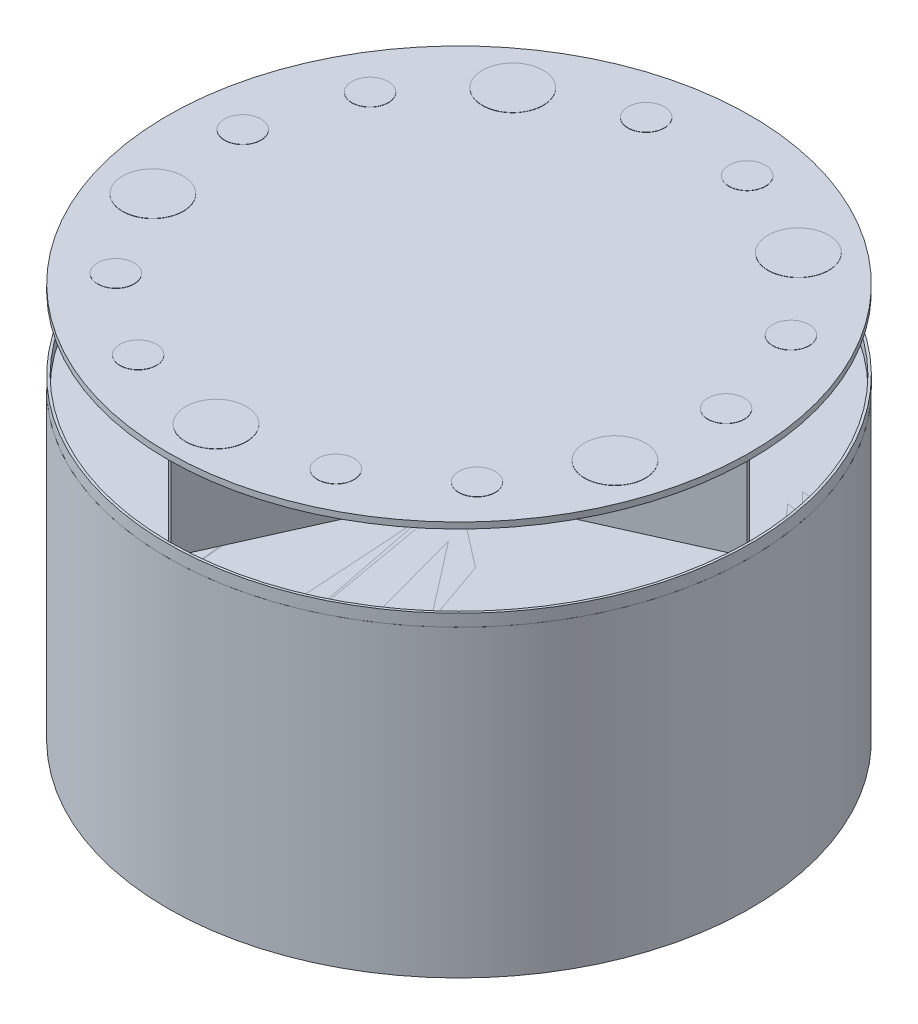
SolidWorks part; units mm, degrees
ref_plane "Front Plane" through (0, 0, 0) normal (0, 0, 1) x (1, 0, 0)
ref_plane "Top Plane" through (0, 0, 0) normal (0, 1, 0) x (1, 0, 0)
ref_plane "Right Plane" through (0, 0, 0) normal (1, 0, 0) x (0, 0, -1)
sketch "Sketch1" plane through (0, 0, 0) normal (0, 1, 0) x (1, 0, 0)
  circle A0 centre (0, 0) radius 304.8
  dimension "D1" = 609.6
extrude "Boss-Extrude1" add sketch "Sketch1" along normal blind 28.575
sketch "Sketch2" plane through (0, 28.575, 0) normal (0, 1, 0) x (1, 0, 0)
  line L0 (245.7653, 171.222) -> (201.7712, 145.822)
  line L1 (-25.4, 298.45) -> (25.4, 298.45)
  line L2 (-25.4, 298.45) -> (-25.4, 247.65)
  line L3 (-25.4, 247.65) -> (25.4, 247.65)
  line L4 (25.4, 298.45) -> (25.4, 247.65)
  line L5 (245.7653, 171.222) -> (271.1653, 127.228)
  line L6 (271.1653, 127.228) -> (227.1712, 101.828)
  line L7 (201.7712, 145.822) -> (227.1712, 101.828)
  line L8 (271.1653, -127.228) -> (227.1712, -101.828)
  line L9 (271.1653, -127.228) -> (245.7653, -171.222)
  line L10 (245.7653, -171.222) -> (201.7712, -145.822)
  line L11 (227.1712, -101.828) -> (201.7712, -145.822)
  line L12 (25.4, -298.45) -> (25.4, -247.65)
  line L13 (25.4, -298.45) -> (-25.4, -298.45)
  line L14 (-25.4, -298.45) -> (-25.4, -247.65)
  line L15 (25.4, -247.65) -> (-25.4, -247.65)
  line L16 (-245.7653, -171.222) -> (-201.7712, -145.822)
  line L17 (-245.7653, -171.222) -> (-271.1653, -127.228)
  line L18 (-271.1653, -127.228) -> (-227.1712, -101.828)
  line L19 (-201.7712, -145.822) -> (-227.1712, -101.828)
  line L20 (-271.1653, 127.228) -> (-227.1712, 101.828)
  line L21 (-271.1653, 127.228) -> (-245.7653, 171.222)
  line L22 (-245.7653, 171.222) -> (-201.7712, 145.822)
  line L23 (-227.1712, 101.828) -> (-201.7712, 145.822)
  point P4 (0, 247.65)
  point P28 (0, 0)
  dimension "D1" = 50.8
  dimension "D2" = 50.8
  dimension "D3" = 0
  dimension "D4" = 247.65
  dimension "D5" = 6
extrude "Boss-Extrude2" add sketch "Sketch2" along normal blind 63.5
sketch "Sketch3" plane through (0, 92.075, 0) normal (0, 1, 0) x (1, 0, 0)
  circle A0 centre (0, 0) radius 304.8
extrude "Boss-Extrude3" add sketch "Sketch3" along normal blind 225.425
sketch "Sketch4" plane through (0, 317.5, 0) normal (0, 1, 0) x (1, 0, 0)
  circle A0 centre (0, 0) radius 88.9
  dimension "D1" = 177.8
sketch "Sketch6" plane through (0, 317.5, 0) normal (0, 1, 0) x (1, 0, 0)
  line L1 (94.2927, 94.2927) -> (302.26, 1.27)
  line L3 (94.2927, -94.2927) -> (302.26, -1.27)
  line L4 (302.26, 1.27) -> (302.26, -1.27)
  line L16 (0, 0) -> (94.2927, -94.2927) construction
  line L17 (0, 0) -> (133.35, 0) construction
  line L19 (94.2927, -94.2927) -> (1.27, -302.26)
  line L20 (1.27, -302.26) -> (-1.27, -302.26)
  line L21 (-94.2927, -94.2927) -> (-1.27, -302.26)
  line L23 (-94.2927, -94.2927) -> (-302.26, -1.27)
  line L24 (-302.26, -1.27) -> (-302.26, 1.27)
  line L25 (-94.2927, 94.2927) -> (-302.26, 1.27)
  line L27 (-94.2927, 94.2927) -> (-1.27, 302.26)
  line L28 (-1.27, 302.26) -> (1.27, 302.26)
  line L29 (94.2927, 94.2927) -> (1.27, 302.26)
  circle A3 centre (0, 0) radius 133.35 construction
  circle A4 centre (0, 0) radius 304.8 construction
  point P22 (-2.5315, 11.0004)
  point P25 (0, 0)
  point P29 (302.26, 0)
  dimension "D1" = 171.45
  dimension "D2" = 45
  dimension "D3" = 4
  dimension "D4" = 2.54
  dimension "D5" = 302.26
extrude "Boss-Extrude8" add sketch "Sketch6" along normal blind 88.9
sketch "Sketch10" plane through (0, 406.4, 0) normal (0, 1, 0) x (1, 0, 0)
  circle A0 centre (0, 0) radius 304.8
extrude "Boss-Extrude11" add sketch "Sketch10" along normal blind 6.35
sketch "Sketch11" plane through (0, 317.5, 0) normal (0, 1, 0) x (1, 0, 0)
  circle A0 centre (0, 0) radius 304.8
  circle A1 centre (0, 0) radius 302.26
  dimension "D1" = 2.54
  dimension "D2" = 609.6
extrude "Boss-Extrude12" add sketch "Sketch11" along normal blind 12.7
sketch "Sketch9" plane through (0, 317.5, 0) normal (0, 1, 0) x (1, 0, 0)
  circle A0 centre (0, 0) radius 304.8165
  circle A1 centre (0, 0) radius 298.1787
  dimension "D1" = 596.3574
extrude "Boss-Extrude10" add sketch "Sketch9" against normal up to surface (317.5 mm away) up to face at (0, 0, 304.8)
sketch "Sketch12" plane through (0, 412.75, 0) normal (0, 1, 0) x (1, 0, 0)
  line L0 (0, 0) -> (103.3111, -232.0405) construction
  line L1 (0, 0) -> (188.7588, -169.9592) construction
  line L2 (0, 0) -> (0, -254) construction
  circle A0 centre (0, -254) radius 31.75
  circle A1 centre (0, 0) radius 254 construction
  circle A2 centre (103.3111, -232.0405) radius 19.05
  circle A3 centre (188.7588, -169.9592) radius 19.05
  dimension "D3" = 63.5
  dimension "D4" = 38.1
  dimension "D5" = 508
  dimension "D1" = 24
  dimension "D2" = 24
extrude "Boss-Extrude13" add sketch "Sketch12" along normal blind 0.254
pattern_circular "CirPattern1" count 5 over 360 about axis through (0, 0, 0) along (0, 1, 0) of "Boss-Extrude13"
